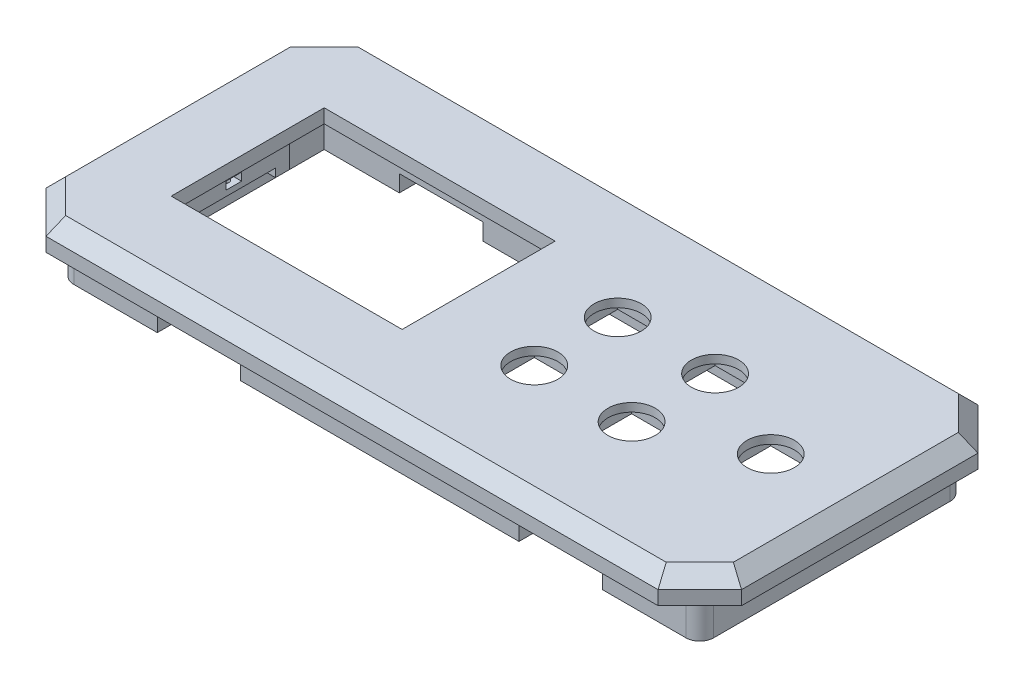
SolidWorks part; units mm, degrees
ref_plane "Front Plane" through (0, 0, 0) normal (0, 0, 1) x (1, 0, 0)
ref_plane "Top Plane" through (0, 0, 0) normal (0, 1, 0) x (1, 0, 0)
ref_plane "Right Plane" through (0, 0, 0) normal (1, 0, 0) x (0, 0, -1)
sketch "Sketch1" plane through (0, 0, 0) normal (0, 1, 0) x (1, 0, 0)
  line L0 (-125, 0) -> (125, 0) construction
  line L1 (-125, 57.5) -> (125, 57.5)
  line L2 (-125, 57.5) -> (-125, -57.5)
  line L3 (-125, -57.5) -> (125, -57.5)
  line L4 (125, 57.5) -> (125, -57.5)
  line L5 (-125, 57.5) -> (125, -57.5) construction
  line L6 (-125, -57.5) -> (125, 57.5) construction
  line L7 (-95, 27.5) -> (-12, 27.5)
  line L8 (-95, 27.5) -> (-95, -27.5)
  line L9 (-95, -27.5) -> (-12, -27.5)
  line L10 (-12, 27.5) -> (-12, -27.5)
  line L11 (-95, 27.5) -> (-12, -27.5) construction
  line L12 (-95, -27.5) -> (-12, 27.5) construction
  circle A0 centre (23, 15) radius 8.5
  circle A1 centre (58, 15) radius 8.5
  circle A2 centre (23, -15) radius 8.5
  circle A3 centre (58, -15) radius 8.5
  circle A4 centre (93, 0) radius 8.5
  point P0 (0, 0)
  point P6 (-53.5, 0)
  dimension "D3" = 17
  dimension "D4" = 17
  dimension "D5" = 17
  dimension "D6" = 17
  dimension "D7" = 35
  dimension "D8" = 35
  dimension "D9" = 30
  dimension "D10" = 15
  dimension "D11" = 35
  dimension "D16" = 17
  dimension "D17" = 35
  dimension "D18" = 35
  dimension "D1" = 250
  dimension "D2" = 30
  dimension "D12" = 30
  dimension "D13" = 30
  dimension "D14" = 55
  dimension "D15" = 83
extrude "Boss-Extrude1" add sketch "Sketch1" along normal blind 10
sketch "Sketch2" plane through (0, 0, 0) normal (0, -1, 0) x (1, 0, 0)
  line L1 (-107, 39.5) -> (107, 39.5)
  line L2 (-107, 39.5) -> (-107, -39.5)
  line L3 (-107, -39.5) -> (107, -39.5)
  line L4 (107, 39.5) -> (107, -39.5)
  line L5 (-107, 39.5) -> (107, -39.5) construction
  line L6 (-107, -39.5) -> (107, 39.5) construction
  line L8 (-125, -57.5) -> (-125, 57.5) construction
  line L9 (-115, 47.5) -> (115, 47.5)
  line L10 (-115, 47.5) -> (-115, -47.5)
  line L11 (-115, -47.5) -> (115, -47.5)
  line L12 (115, 47.5) -> (115, -47.5)
  line L13 (-115, 47.5) -> (115, -47.5) construction
  line L14 (-115, -47.5) -> (115, 47.5) construction
  line L15 (-125, 57.5) -> (125, 57.5) construction
  point P0 (0, 0)
  point P10 (0, 0)
  dimension "D1" = 10
  dimension "D2" = 10
  dimension "D3" = 8
  dimension "D4" = 8
extrude "Boss-Extrude2" add sketch "Sketch2" along normal blind 15
sketch "Sketch3" plane through (0, 0, 0) normal (0, -1, 0) x (1, 0, 0)
  line L1 (10.5, 27.5) -> (35.5, 27.5)
  line L2 (10.5, 27.5) -> (10.5, 2.5)
  line L3 (10.5, 2.5) -> (35.5, 2.5)
  line L4 (35.5, 27.5) -> (35.5, 2.5)
  line L5 (10.5, 27.5) -> (35.5, 2.5) construction
  line L6 (10.5, 2.5) -> (35.5, 27.5) construction
  line L7 (45.5, 27.5) -> (70.5, 27.5)
  line L8 (45.5, 27.5) -> (45.5, 2.5)
  line L9 (45.5, 2.5) -> (70.5, 2.5)
  line L10 (70.5, 27.5) -> (70.5, 2.5)
  line L11 (45.5, 27.5) -> (70.5, 2.5) construction
  line L12 (45.5, 2.5) -> (70.5, 27.5) construction
  line L13 (10.5, -2.5) -> (35.5, -2.5)
  line L14 (10.5, -2.5) -> (10.5, -27.5)
  line L15 (10.5, -27.5) -> (35.5, -27.5)
  line L16 (35.5, -2.5) -> (35.5, -27.5)
  line L17 (10.5, -2.5) -> (35.5, -27.5) construction
  line L18 (10.5, -27.5) -> (35.5, -2.5) construction
  line L19 (45.5, -2.5) -> (70.5, -2.5)
  line L20 (45.5, -2.5) -> (45.5, -27.5)
  line L21 (45.5, -27.5) -> (70.5, -27.5)
  line L22 (70.5, -2.5) -> (70.5, -27.5)
  line L23 (45.5, -2.5) -> (70.5, -27.5) construction
  line L24 (45.5, -27.5) -> (70.5, -2.5) construction
  line L25 (80.5, 12.5) -> (105.5, 12.5)
  line L26 (80.5, 12.5) -> (80.5, -12.5)
  line L27 (80.5, -12.5) -> (105.5, -12.5)
  line L28 (105.5, 12.5) -> (105.5, -12.5)
  line L29 (80.5, 12.5) -> (105.5, -12.5) construction
  line L30 (80.5, -12.5) -> (105.5, 12.5) construction
  point P0 (23, 15)
  point P6 (58, 15)
  point P12 (23, -15)
  point P18 (58, -15)
  point P24 (93, 0)
  dimension "D1" = 25
  dimension "D2" = 25
  dimension "D3" = 25
  dimension "D4" = 25
  dimension "D5" = 25
  dimension "D6" = 25
  dimension "D7" = 25
  dimension "D8" = 25
  dimension "D9" = 25
  dimension "D10" = 25
extrude "Cut-Extrude1" cut sketch "Sketch3" against normal blind 7
sketch "Sketch4" plane through (0, 0, 0) normal (0, -1, 0) x (1, 0, 0)
  line L1 (-95, 27.5) -> (-12, 27.5)
  line L2 (-95, 27.5) -> (-95, -27.5)
  line L3 (-95, -27.5) -> (-12, -27.5)
  line L4 (-12, 27.5) -> (-12, -27.5)
  line L5 (-100, 32.5) -> (-7, 32.5)
  line L6 (-100, 32.5) -> (-100, -32.5)
  line L7 (-100, -32.5) -> (-7, -32.5)
  line L8 (-7, 32.5) -> (-7, -32.5)
  dimension "D1" = 5
  dimension "D2" = 5
  dimension "D3" = 5
  dimension "D4" = 5
extrude "Cut-Extrude2" cut sketch "Sketch4" against normal blind 5
sketch "Sketch5" plane through (0, 0, 0) normal (0, -1, 0) x (1, 0, 0)
  line L0 (-7, -32.5) -> (-7, 32.5) construction
  line L10 (-100, 0) -> (-115, 0) construction
  line L11 (-100, 32.5) -> (-100, -32.5) construction
  line L12 (-115, 47.5) -> (-115, -47.5) construction
  line L26 (-107, 39.5) -> (-107, -39.5) construction
  line L27 (-107, 20) -> (-100, 20)
  line L29 (-107, 20) -> (-107, -20)
  line L30 (-107, -20) -> (-100, -20)
  line L31 (-100, 20) -> (-100, -20)
  line L32 (-107, 20) -> (-100, -20) construction
  line L33 (-107, -20) -> (-100, 20) construction
  line L34 (-7, 20.3538) -> (3, 20.3538)
  line L39 (-7, 20.3538) -> (-7, -19.6462)
  line L40 (-7, -19.6462) -> (3, -19.6462)
  line L46 (-100, 15) -> (-107, 15)
  line L47 (3, 20.3538) -> (3, -19.6462)
  line L48 (-7, 0.3538) -> (3, 0.3538) construction
  line L49 (-100, 15) -> (-100, -15)
  line L50 (-7, 15.3538) -> (3, 15.3538)
  line L51 (-7, 15.3538) -> (-7, -14.6462)
  line L52 (-7, -14.6462) -> (3, -14.6462)
  line L53 (3, 15.3538) -> (3, -14.6462)
  line L54 (-100, -15) -> (-107, -15)
  line L55 (-107, 15) -> (-107, -15)
  point P0 (-1.0455, 0)
  point P21 (-111, 0)
  point P22 (-103.5, 0)
  point P30 (-102.2774, 0)
  line M13 (-100, -32.5) -> (-100, 32.5)
  line M15 (-7, 32.5) -> (-7, -32.5)
  line M39 (-107, 39.5) -> (-107, -39.5)
  dimension "D1" = 20
  dimension "D2" = 20
  dimension "D3" = 10
  dimension "D4" = 0
  dimension "D5" = 0
  dimension "D6" = 20
  dimension "D7" = 5
  dimension "D8" = 5
  dimension "D9" = 0
  dimension "D10" = 5
  dimension "D11" = 5
  dimension "D12" = 0
extrude "Boss-Extrude3" add sketch "Sketch5" along normal blind 8 contours L46 L31 L27 M39 | L54 L30 M13 M39 | L50 L47 L34 M15 | L52 L40 L47 M15
sketch "Sketch7" plane through (0, 0, 0) normal (0, -1, 0) x (1, 0, 0)
  line L1 (-100, 15) -> (-107, 15)
  line L2 (-100, 15) -> (-100, -15)
  line L3 (-100, -15) -> (-107, -15)
  line L4 (-107, 15) -> (-107, -15)
  line L5 (-7, 15.3538) -> (3, 15.3538)
  line L6 (-7, 15.3538) -> (-7, -14.6462)
  line L7 (-7, -14.6462) -> (3, -14.6462)
  line L8 (3, 15.3538) -> (3, -14.6462)
extrude "Boss-Extrude4" add sketch "Sketch7" along normal blind 5
sketch "Sketch8" plane through (-7, 0, 0) normal (-1, 0, 0) x (0, 0, 1)
  line L0 (-19.6462, 0) -> (20.3538, 0) construction
  line L1 (0, 0) -> (0, -5) construction
  line L2 (15.3538, -5) -> (-14.6462, -5) construction
  line L4 (-2.8, -0.2) -> (2.8, -0.2)
  line L5 (-2.8, -0.2) -> (-2.8, -3)
  line L6 (-2.8, -3) -> (2.8, -3)
  line L7 (2.8, -0.2) -> (2.8, -3)
  line L8 (-2.8, -0.2) -> (2.8, -3) construction
  line L9 (-2.8, -3) -> (2.8, -0.2) construction
  point P9 (0, -1.6)
  dimension "D1" = 2.8
  dimension "D2" = 5.6
  dimension "D3" = 2
extrude "Cut-Extrude7" cut sketch "Sketch8" against normal blind 6.6
sketch "Sketch9" plane through (-100, 0, 0) normal (1, 0, 0) x (0, 0, -1)
  line L0 (-20, 0) -> (20, 0) construction
  line L1 (0, 0) -> (0, -5) construction
  line L2 (15, -5) -> (-15, -5) construction
  line L4 (-2.8, -0.2) -> (2.8, -0.2)
  line L5 (-2.8, -0.2) -> (-2.8, -3)
  line L6 (-2.8, -3) -> (2.8, -3)
  line L7 (2.8, -0.2) -> (2.8, -3)
  line L8 (-2.8, -0.2) -> (2.8, -3) construction
  line L9 (-2.8, -3) -> (2.8, -0.2) construction
  point P8 (0, -1.6)
  dimension "D1" = 2.8
  dimension "D2" = 5.6
  dimension "D3" = 2
extrude "Cut-Extrude8" cut sketch "Sketch9" against normal blind 6.6
sketch "Sketch10" plane through (0, -0.2, 0) normal (0, -1, 0) x (1, 0, 0)
  line L0 (-0.4, 0) -> (-7, 0) construction
  line L1 (-0.4, 2.8) -> (-0.4, -2.8) construction
  line L2 (-7, 2.8) -> (-7, -2.8) construction
  line L3 (-106.7164, 0) -> (-100, 0) construction
  line L4 (-100, -2.8) -> (-100, 2.8) construction
  line L6 (-100.4184, 0) -> (-101.9484, 2.65)
  line L7 (-101.9484, 2.65) -> (-105.0084, 2.65)
  line L8 (-105.0084, 2.65) -> (-106.5384, 0)
  line L9 (-106.5384, 0) -> (-105.0084, -2.65)
  line L10 (-105.0084, -2.65) -> (-101.9484, -2.65)
  line L11 (-101.9484, -2.65) -> (-100.4184, 0)
  line L12 (-6.76, 0) -> (-5.23, -2.65)
  line L13 (-5.23, -2.65) -> (-2.17, -2.65)
  line L14 (-2.17, -2.65) -> (-0.64, 0)
  line L15 (-0.64, 0) -> (-2.17, 2.65)
  line L16 (-2.17, 2.65) -> (-5.23, 2.65)
  line L17 (-5.23, 2.65) -> (-6.76, 0)
  circle A0 centre (-103.4784, 0) radius 2.65 construction
  circle A1 centre (-3.7, 0) radius 2.65 construction
  circle A2 centre (-3.7, 0) radius 1.65
  circle A3 centre (-103.4784, 0) radius 1.65
  dimension "D3" = 3.3
  dimension "D4" = 3.3
  dimension "D1" = 5.3
  dimension "D2" = 5.3
extrude "Cut-Extrude9" cut sketch "Sketch10" against normal through all both and the other way through all contours A2 | A3
sketch "Sketch11" plane through (0, 10, 0) normal (0, 1, 0) x (1, 0, 0)
  circle A0 centre (-3.7, 0) radius 1.65
  circle A1 centre (-103.4784, 0) radius 1.65
extrude "Boss-Extrude5" add sketch "Sketch11" against normal blind 3
sketch "Sketch12" plane through (0, -8, 0) normal (0, -1, 0) x (1, 0, 0)
  line L0 (3, -14.6462) -> (3, -19.6462) construction
  line L1 (-7, -14.6462) -> (3, -14.6462)
  line L2 (-7, -14.6462) -> (-7, -15.1462)
  line L3 (-7, -15.1462) -> (3, -15.1462)
  line L4 (3, -14.6462) -> (3, -15.1462)
  dimension "D1" = 0.5
extrude "Cut-Extrude10" cut sketch "Sketch12" against normal blind 3
sketch "Sketch13" plane through (0, -15, 0) normal (0, -1, 0) x (1, 0, 0)
  line L0 (115, 47.5) -> (-115, 47.5) construction
  line L1 (-80, 47.5) -> (-50, 47.5)
  line L2 (-80, 47.5) -> (-80, 39.5)
  line L3 (-80, 39.5) -> (-50, 39.5)
  line L4 (-50, 47.5) -> (-50, 39.5)
  line L5 (107, 39.5) -> (-107, 39.5) construction
  line L6 (-107, -39.5) -> (107, -39.5) construction
  line L7 (50, 47.5) -> (80, 47.5)
  line L8 (50, 47.5) -> (50, 39.5)
  line L9 (50, 39.5) -> (80, 39.5)
  line L10 (80, 47.5) -> (80, 39.5)
  line L11 (-80, -39.5) -> (-50, -39.5)
  line L12 (-80, -39.5) -> (-80, -47.5)
  line L13 (-80, -47.5) -> (-50, -47.5)
  line L14 (-50, -39.5) -> (-50, -47.5)
  line L15 (-115, -47.5) -> (115, -47.5) construction
  line L16 (0, 47.5) -> (0, -47.5) construction
  line L17 (50, -39.5) -> (80, -39.5)
  line L18 (50, -39.5) -> (50, -47.5)
  line L19 (50, -47.5) -> (80, -47.5)
  line L20 (80, -39.5) -> (80, -47.5)
  line L21 (-115, -47.5) -> (115, -47.5) construction
  dimension "D1" = 50
  dimension "D2" = 50
  dimension "D3" = 50
  dimension "D4" = 50
  dimension "D5" = 30
  dimension "D6" = 30
  dimension "D7" = 30
  dimension "D8" = 30
extrude "Cut-Extrude11" cut sketch "Sketch13" against normal blind 6
sketch "Sketch14" plane through (0, 0, 47.5) normal (0, 0, 1) x (1, 0, 0)
  line L1 (-65, -9) -> (-65, 0) construction
  line L2 (-50, -9) -> (-80, -9) construction
  line L3 (115, 0) -> (-115, 0) construction
  line L4 (65, -9) -> (65, 0) construction
  line L5 (80, -9) -> (50, -9) construction
  line L7 (-67.8, -3.2) -> (-62.2, -3.2)
  line L8 (-67.8, -3.2) -> (-67.8, -6)
  line L9 (-67.8, -6) -> (-62.2, -6)
  line L10 (-62.2, -3.2) -> (-62.2, -6)
  line L11 (-67.8, -3.2) -> (-62.2, -6) construction
  line L12 (-67.8, -6) -> (-62.2, -3.2) construction
  line L13 (62.2, -3.2) -> (67.8, -3.2)
  line L14 (62.2, -3.2) -> (62.2, -6)
  line L15 (62.2, -6) -> (67.8, -6)
  line L16 (67.8, -3.2) -> (67.8, -6)
  line L17 (62.2, -3.2) -> (67.8, -6) construction
  line L18 (62.2, -6) -> (67.8, -3.2) construction
  point P10 (-65, -4.6)
  point P15 (65, -4.6)
  dimension "D1" = 2.8
  dimension "D2" = 5.6
  dimension "D3" = 2.8
  dimension "D4" = 5.6
  dimension "D5" = 3
  dimension "D6" = 3
extrude "Cut-Extrude12" cut sketch "Sketch14" against normal blind 6.6
sketch "Sketch15" plane through (0, -3.2, 0) normal (0, -1, 0) x (1, 0, 0)
  line L0 (-65, 47.5) -> (-65, 40.9) construction
  line L1 (-62.2, 47.5) -> (-67.8, 47.5) construction
  line L2 (-62.2, 40.9) -> (-67.8, 40.9) construction
  line L3 (65, 47.5) -> (65, 40.9) construction
  line L4 (-65, 40.9668) -> (-62.2, 42.5834)
  line L5 (-62.2, 42.5834) -> (-62.2, 45.8166)
  line L6 (-62.2, 45.8166) -> (-65, 47.4332)
  line L7 (-65, 47.4332) -> (-67.8, 45.8166)
  line L8 (-67.8, 45.8166) -> (-67.8, 42.5834)
  line L9 (-67.8, 42.5834) -> (-65, 40.9668)
  line L10 (67.8, 47.5) -> (62.2, 47.5) construction
  line L11 (67.8, 40.9) -> (62.2, 40.9) construction
  line L13 (65, 40.9668) -> (67.8, 42.5834)
  line L14 (67.8, 42.5834) -> (67.8, 45.8166)
  line L15 (67.8, 45.8166) -> (65, 47.4332)
  line L16 (65, 47.4332) -> (62.2, 45.8166)
  line L17 (62.2, 45.8166) -> (62.2, 42.5834)
  line L18 (62.2, 42.5834) -> (65, 40.9668)
  circle A0 centre (-65, 44.2) radius 2.8 construction
  circle A1 centre (-65, 44.2) radius 1.65
  circle A2 centre (65, 44.2) radius 2.8 construction
  circle A3 centre (65, 44.2) radius 1.65
  dimension "D2" = 3.3
  dimension "D4" = 3.3
  dimension "D1" = 5.6
  dimension "D3" = 5.6
extrude "Cut-Extrude13" cut sketch "Sketch15" against normal through all both and the other way through all contours A3 | A1
sketch "Sketch16" plane through (0, 0, -47.5) normal (0, 0, -1) x (-1, 0, 0)
  line L0 (65, -9) -> (65, 0) construction
  line L1 (80, -9) -> (50, -9) construction
  line L2 (115, 0) -> (-115, 0) construction
  line L3 (-65, -9) -> (-65, 0) construction
  line L4 (-50, -9) -> (-80, -9) construction
  line L5 (-125, 0) -> (125, 0) construction
  line L7 (-67.8, -3.2) -> (-62.2, -3.2)
  line L8 (-67.8, -3.2) -> (-67.8, -6)
  line L9 (-67.8, -6) -> (-62.2, -6)
  line L10 (-62.2, -3.2) -> (-62.2, -6)
  line L11 (-67.8, -3.2) -> (-62.2, -6) construction
  line L12 (-67.8, -6) -> (-62.2, -3.2) construction
  line L13 (62.2, -3.2) -> (67.8, -3.2)
  line L14 (62.2, -3.2) -> (62.2, -6)
  line L15 (62.2, -6) -> (67.8, -6)
  line L16 (67.8, -3.2) -> (67.8, -6)
  line L17 (62.2, -3.2) -> (67.8, -6) construction
  line L18 (62.2, -6) -> (67.8, -3.2) construction
  point P12 (-65, -4.6)
  point P17 (65, -4.6)
  dimension "D1" = 5.6
  dimension "D2" = 2.8
  dimension "D3" = 3
  dimension "D4" = 2.8
  dimension "D5" = 5.6
  dimension "D6" = 3
extrude "Cut-Extrude14" cut sketch "Sketch16" against normal blind 6.6
sketch "Sketch17" plane through (0, -3.2, 0) normal (0, -1, 0) x (1, 0, 0)
  line L0 (65, -40.9) -> (65, -47.5) construction
  line L1 (62.2, -40.9) -> (67.8, -40.9) construction
  line L2 (62.2, -47.5) -> (67.8, -47.5) construction
  line L3 (-65, -40.9) -> (-65, -47.5) construction
  line L4 (65, -47.4332) -> (67.8, -45.8166)
  line L5 (67.8, -45.8166) -> (67.8, -42.5834)
  line L6 (67.8, -42.5834) -> (65, -40.9668)
  line L7 (65, -40.9668) -> (62.2, -42.5834)
  line L8 (62.2, -42.5834) -> (62.2, -45.8166)
  line L9 (62.2, -45.8166) -> (65, -47.4332)
  line L10 (-67.8, -40.9) -> (-62.2, -40.9) construction
  line L11 (-67.8, -47.5) -> (-62.2, -47.5) construction
  line L13 (-65, -47.2315) -> (-62.2, -45.615)
  line L14 (-62.2, -45.615) -> (-62.2, -42.3818)
  line L15 (-62.2, -42.3818) -> (-65, -40.7652)
  line L16 (-65, -40.7652) -> (-67.8, -42.3818)
  line L17 (-67.8, -42.3818) -> (-67.8, -45.615)
  line L18 (-67.8, -45.615) -> (-65, -47.2315)
  circle A0 centre (65, -44.2) radius 2.8 construction
  circle A1 centre (65, -44.2) radius 1.65
  circle A2 centre (-65, -43.9984) radius 2.8 construction
  circle A3 centre (-65, -43.9984) radius 1.65
  point P7 (67.8, -44.2)
  point P23 (-62.2, -43.9984)
  dimension "D2" = 3.3
  dimension "D4" = 3.3
  dimension "D1" = 5.6
  dimension "D3" = 5.6
extrude "Cut-Extrude15" cut sketch "Sketch17" against normal through all both and the other way through all contours A3 | A1
sketch "Sketch18" plane through (0, 10, 0) normal (0, 1, 0) x (1, 0, 0)
  circle A0 centre (-65, 43.9984) radius 1.65
  circle A1 centre (65, 44.2) radius 1.65
  circle A2 centre (-65, -44.2) radius 1.65
  circle A3 centre (65, -44.2) radius 1.65
extrude "Boss-Extrude6" add sketch "Sketch18" against normal blind 4
chamfer "Chamfer1" distance 15 angle 45 4 edges at (-125, 5, -57.5) (125, 5, -57.5) (125, 5, 57.5) (-125, 5, 57.5)
chamfer "Chamfer2" distance 5 angle 45 8 edges at (117.5, 10, 50) (125, 10, 0) (117.5, 10, -50) (0, 10, -57.5) (-117.5, 10, -50) (0, 10, 57.5) (-125, 10, 0) (-117.5, 10, 50)
fillet "Fillet1" radius 5 4 edges at (-115, -7.5, 47.5) (-115, -7.5, -47.5) (115, -7.5, -47.5) (115, -7.5, 47.5)
